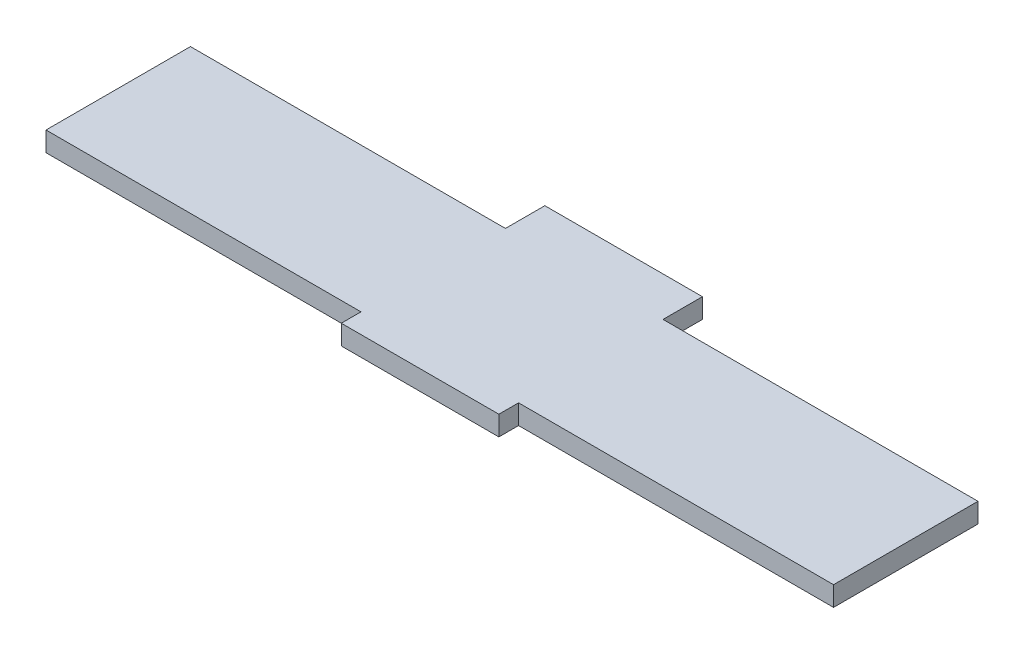
SolidWorks part; units mm, degrees
ref_plane "Front Plane" through (0, 0, 0) normal (0, 0, 1) x (1, 0, 0)
ref_plane "Top Plane" through (0, 0, 0) normal (0, 1, 0) x (1, 0, 0)
ref_plane "Right Plane" through (0, 0, 0) normal (1, 0, 0) x (0, 0, -1)
sketch "Sketch1" plane through (0, 0, 0) normal (0, 1, 0) x (1, 0, 0)
  line L1 (-119.9354, 22) -> (0, 22)
  line L2 (-119.9354, 22) -> (-119.9354, 0)
  line L3 (-119.9354, 0) -> (0, 0)
  line L4 (0, 22) -> (0, 0)
  line L5 (-71.9677, 22) -> (-47.9677, 22)
  line L6 (-71.9677, 22) -> (-71.9677, 28)
  line L7 (-71.9677, 28) -> (-47.9677, 28)
  line L8 (-47.9677, 22) -> (-47.9677, 28)
  line L9 (-71.9677, 0) -> (-47.9677, 0)
  line L10 (-71.9677, 0) -> (-71.9677, -3)
  line L11 (-71.9677, -3) -> (-47.9677, -3)
  line L12 (-47.9677, 0) -> (-47.9677, -3)
  point P13 (-59.9677, -3)
  point P14 (-59.9677, 0)
  dimension "D1" = 22
  dimension "D2" = 119.9354
  dimension "D3" = 24
  dimension "D4" = 3
  dimension "D5" = 6
extrude "Boss-Extrude1" add sketch "Sketch1" along normal blind 3 contours L12 L3 L10 L11 | L4 L1 L2 L3 | L1 L8 L7 L6
equation "\"D2@Sketch1\"=\"x\""
equation "\"x\" = 120 / ( cos ( \"angle\" ) ) - 2 * \"thick\" * cos ( 90 - \"angle\" )"
equation "\"angle\"= 5"
equation "\"thick\"=3"
equation "\"D1@Boss-Extrude1\"=\"thick\""
